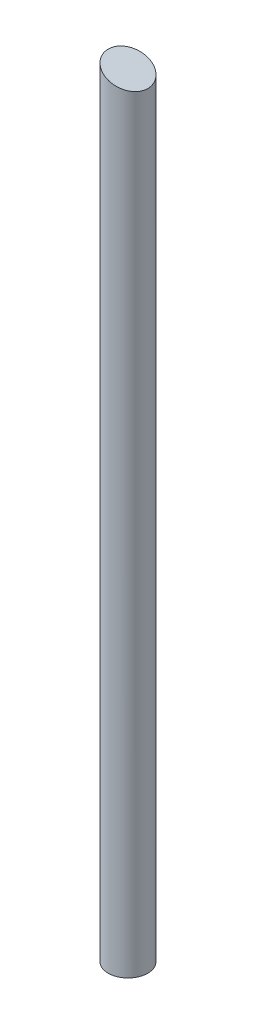
SolidWorks part; units mm, degrees
ref_plane "前基準面" through (0, 0, 0) normal (0, 0, 1) x (1, 0, 0)
ref_plane "上基準面" through (0, 0, 0) normal (0, 1, 0) x (1, 0, 0)
ref_plane "右基準面" through (0, 0, 0) normal (1, 0, 0) x (0, 0, -1)
sketch "草圖1" plane through (0, 0, 0) normal (0, 1, 0) x (1, 0, 0)
  circle A0 centre (0, 0) radius 3.5
  dimension "D1" = 7
extrude "填料-伸長1" add sketch "草圖1" along normal blind 138
sketch "草圖2" plane through (0, 0, 0) normal (0, 0, 1) x (1, 0, 0)
  line L0 (-3.5, 138) -> (3.5, 135.4522)
  line L1 (-3.5, 138) -> (3.5, 138)
  line L2 (3.5, 138) -> (3.5, 135.4522)
  dimension "D1" = 20
extrude "除料-伸長1" cut sketch "草圖2" against normal mid plane 10
